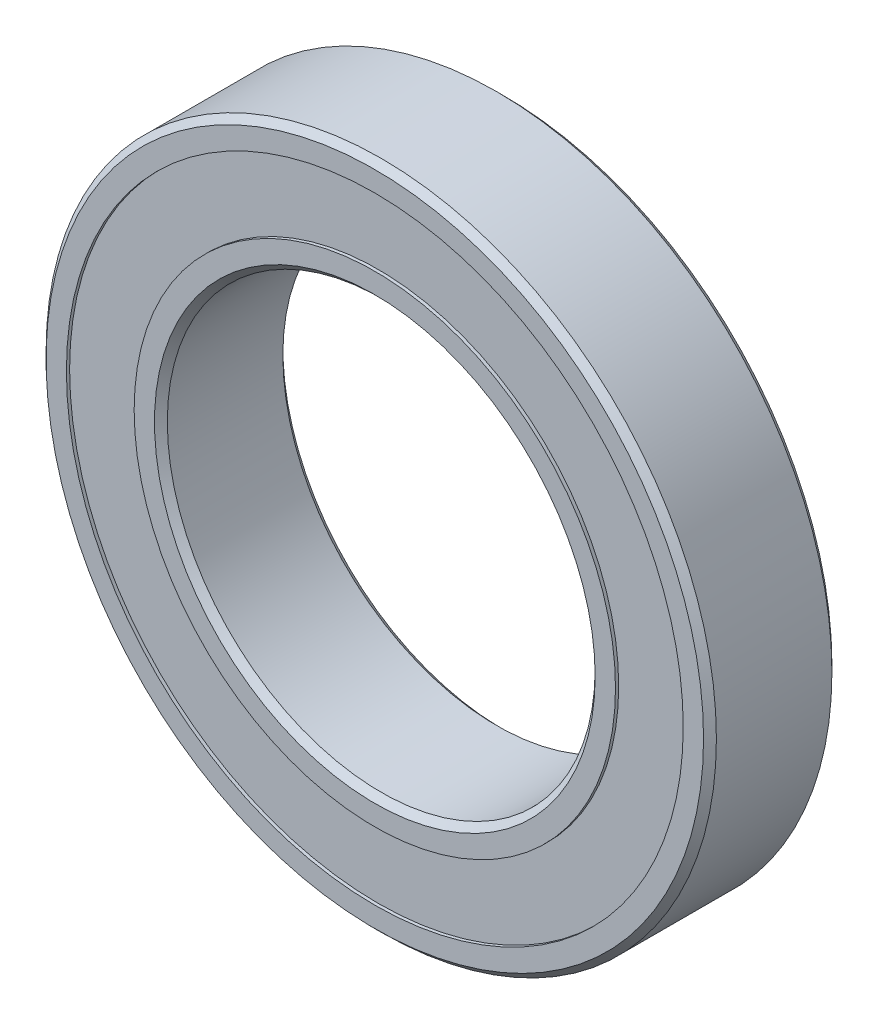
SolidWorks part; units mm, degrees
ref_plane "Front Plane" through (0, 0, 0) normal (0, 0, 1) x (1, 0, 0)
ref_plane "Top Plane" through (0, 0, 0) normal (0, 1, 0) x (1, 0, 0)
ref_plane "Right Plane" through (0, 0, 0) normal (1, 0, 0) x (0, 0, -1)
sketch "Sketch1" plane through (0, 0, 0) normal (0, 0, 1) x (1, 0, 0)
  circle A0 centre (0, 0) radius 23.5 construction
  circle A1 centre (0, 0) radius 14.9995 construction
  dimension "OD" = 47
  dimension "ID" = 29.999
sketch "Sketch2" plane through (0, 0, 0) normal (1, 0, 0) x (0, 0, -1)
  line L0 (-4.5, 0) -> (4.5, 0) construction
  line L1 (0, 23.5) -> (0, -23.5) construction
  line L2 (4.05, 23.5) -> (-4.05, 23.5) construction
  line L3 (-4.05, 23.5) -> (-4.5, 23.05) construction
  line L4 (-4.5, 23.05) -> (-4.5, 21.6247) construction
  line L5 (-4.5, 21.6247) -> (-2, 21.6247) construction
  line L6 (4.5, 21.6247) -> (2, 21.6247) construction
  line L7 (4.5, 23.05) -> (4.5, 21.6247) construction
  line L8 (4.05, 23.5) -> (4.5, 23.05) construction
  line L9 (0, 23.5) -> (0, 19.2498) construction
  line L10 (0, 19.2498) -> (0, 14.9995) construction
  line L11 (4.5, 19.2498) -> (-4.5, 19.2498) construction
  line L12 (-4.5, 15.4495) -> (-4.5, 16.8748) construction
  line L13 (-4.05, 14.9995) -> (-4.5, 15.4495) construction
  line L14 (4.05, 14.9995) -> (-4.05, 14.9995) construction
  line L15 (4.05, 14.9995) -> (4.5, 15.4495) construction
  line L16 (4.5, 15.4495) -> (4.5, 16.8748) construction
  line L17 (4.5, 16.8748) -> (2, 16.8748) construction
  line L18 (-4.5, 16.8748) -> (-2, 16.8748) construction
  line L19 (-4.5, 15) -> (-4.5, -15) construction
  line L20 (4.5, 23.5) -> (4.5, -23.5) construction
  arc A0 (-2, 21.6247) -> (2, 21.6247) centre (0, 19.2498) cw construction
  arc A1 (-2, 16.8748) -> (2, 16.8748) centre (0, 19.2498) ccw construction
  point P14 (0, 14.9995)
  point P18 (0, 19.2498)
  dimension "Approx. Ball Dia." = 6.2099
  dimension "D1" = 45
  dimension "D2" = 0.45
  dimension "D3" = 4
  dimension "D4" = 2.375
  dimension "Width" = 9
  dimension "For Shaft Diameter" = 30
  dimension "For Housing ID" = 47
sketch "Sketch3" plane through (0, 0, 0) normal (1, 0, 0) x (0, 0, -1)
  line L0 (-4.5, 23.05) -> (-4.5, 21.6247) construction
  line L1 (-4.05, 23.5) -> (-4.5, 23.05) construction
  line L2 (4.05, 23.5) -> (-4.05, 23.5) construction
  line L3 (4.05, 23.5) -> (4.5, 23.05) construction
  line L4 (4.5, 23.05) -> (4.5, 21.6247) construction
  line L5 (4.5, 21.6247) -> (2, 21.6247) construction
  line L6 (-4.5, 21.6247) -> (-2, 21.6247) construction
  line L7 (-4.5, 23.05) -> (-4.5, 21.6247)
  line L8 (-4.05, 23.5) -> (-4.5, 23.05)
  line L9 (4.05, 23.5) -> (-4.05, 23.5)
  line L10 (4.05, 23.5) -> (4.5, 23.05)
  line L11 (4.5, 23.05) -> (4.5, 21.6247)
  line L12 (4.5, 21.6247) -> (2, 21.6247)
  line L13 (-4.5, 21.6247) -> (-2, 21.6247)
  line L14 (-4.5, 15.4495) -> (-4.5, 16.8748) construction
  line L15 (-4.05, 14.9995) -> (-4.5, 15.4495) construction
  line L16 (4.05, 14.9995) -> (-4.05, 14.9995) construction
  line L17 (4.05, 14.9995) -> (4.5, 15.4495) construction
  line L18 (4.5, 15.4495) -> (4.5, 16.8748) construction
  line L19 (4.5, 16.8748) -> (2, 16.8748) construction
  line L20 (-4.5, 16.8748) -> (-2, 16.8748) construction
  line L21 (-4.5, 15.4495) -> (-4.5, 16.8748)
  line L22 (-4.05, 14.9995) -> (-4.5, 15.4495)
  line L23 (4.05, 14.9995) -> (-4.05, 14.9995)
  line L24 (4.05, 14.9995) -> (4.5, 15.4495)
  line L25 (4.5, 15.4495) -> (4.5, 16.8748)
  line L26 (4.5, 16.8748) -> (2, 16.8748)
  line L27 (-4.5, 16.8748) -> (-2, 16.8748)
  arc A0 (2, 21.6247) -> (-2, 21.6247) centre (0, 19.2498) ccw construction
  arc A1 (2, 21.6247) -> (-2, 21.6247) centre (0, 19.2498) ccw
  arc A2 (-2, 16.8748) -> (2, 16.8748) centre (0, 19.2498) ccw construction
  arc A3 (-2, 16.8748) -> (2, 16.8748) centre (0, 19.2498) ccw
revolve "Revolve1" add sketch "Sketch3" angle 360 about L0
sketch "Sketch4" plane through (0, 0, 0) normal (1, 0, 0) x (0, 0, -1)
  line L0 (-3.1049, 19.2498) -> (3.1049, 19.2498)
  arc A2 (-3.1049, 19.2498) -> (3.1049, 19.2498) centre (0, 19.2498) cw
  arc A3 (2, 21.6247) -> (-2, 21.6247) centre (0, 19.2498) ccw construction
revolve "Revolve2" add sketch "Sketch4" angle 360 about L0
pattern_circular "CirPattern1" count 12 over 360 about axis through (0, 0, 0) along (0, 0, 1) of bodies 104
sketch "Sketch5" plane through (0, 0, 0) normal (1, 0, 0) x (0, 0, -1)
  line L0 (-4.5, 21.6247) -> (-2, 21.6247) construction
  line L1 (-4.275, 21.6247) -> (-3.1049, 21.6247)
  line L2 (-4.275, 21.6247) -> (-4.275, 16.8748)
  line L3 (-4.275, 16.8748) -> (-3.1049, 16.8748)
  line L4 (-3.1049, 21.6247) -> (-3.1049, 16.8748)
  line L6 (4.5, 21.6247) -> (2, 21.6247) construction
  line L7 (4.275, 21.6247) -> (3.1049, 21.6247)
  line L8 (4.275, 21.6247) -> (4.275, 16.8748)
  line L9 (4.275, 16.8748) -> (3.1049, 16.8748)
  line L10 (3.1049, 21.6247) -> (3.1049, 16.8748)
  line L12 (-4.05, 23.5) -> (-4.5, 23.05) construction
  line L13 (-4.5, 16.8748) -> (-2, 16.8748) construction
  line L14 (4.5, 16.8748) -> (2, 16.8748) construction
  point P18 (-4.275, 23.275)
revolve "Revolve3" add sketch "Sketch5" angle 360 about L0
equation "\"D2@Sketch2\"= \"Width@Sketch2\" * .05"
equation "\"D3@Sketch2\"=\"Width@Sketch2\" / 2.25"
equation "\"D4@Sketch2\"=( \"OD@Sketch1\" - \"Width@Sketch2\" ) *.5 *.125"
equation "\"Approx. No. of Balls\"= ( pi * \"OD@Sketch1\" ) * .5 / \"Approx. Ball Dia.@Sketch2\""
equation "\"Balls@CirPattern1\"=\"Approx. No. of Balls\""
